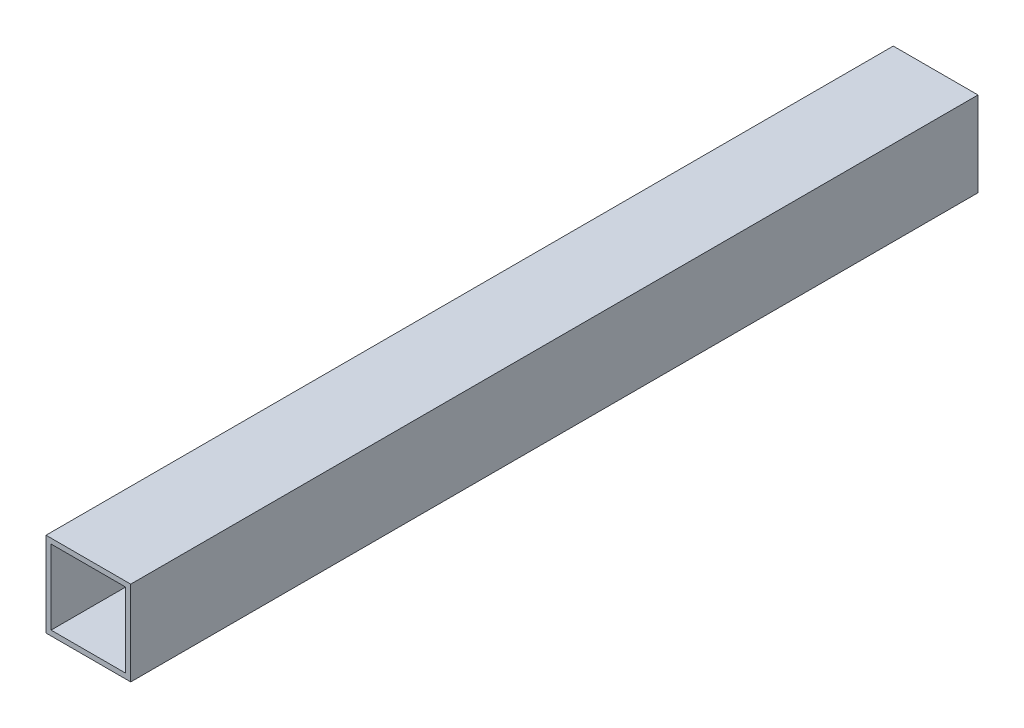
SolidWorks part; units mm, degrees
ref_plane "前视基准面" through (0, 0, 0) normal (0, 0, 1) x (1, 0, 0)
ref_plane "上视基准面" through (0, 0, 0) normal (0, 1, 0) x (1, 0, 0)
ref_plane "右视基准面" through (0, 0, 0) normal (1, 0, 0) x (0, 0, -1)
sketch "草图1" plane through (0, 0, 0) normal (0, 0, 1) x (1, 0, 0)
  line L0 (-22, -22) -> (-22, 22)
  line L1 (-25, -25) -> (25, -25)
  line L2 (-25, -25) -> (-25, 25)
  line L3 (-25, 25) -> (25, 25)
  line L4 (25, -25) -> (25, 25)
  line L5 (-25, -25) -> (25, 25) construction
  line L6 (-25, 25) -> (25, -25) construction
  line L7 (-22, 22) -> (22, 22)
  line L8 (22, -22) -> (22, 22)
  line L9 (-22, -22) -> (22, -22)
  point P0 (0, 0)
  dimension "D1" = 50
  dimension "D2" = 50
  dimension "D3" = 3
extrude "凸台-拉伸1" add sketch "草图1" along normal mid plane 500
